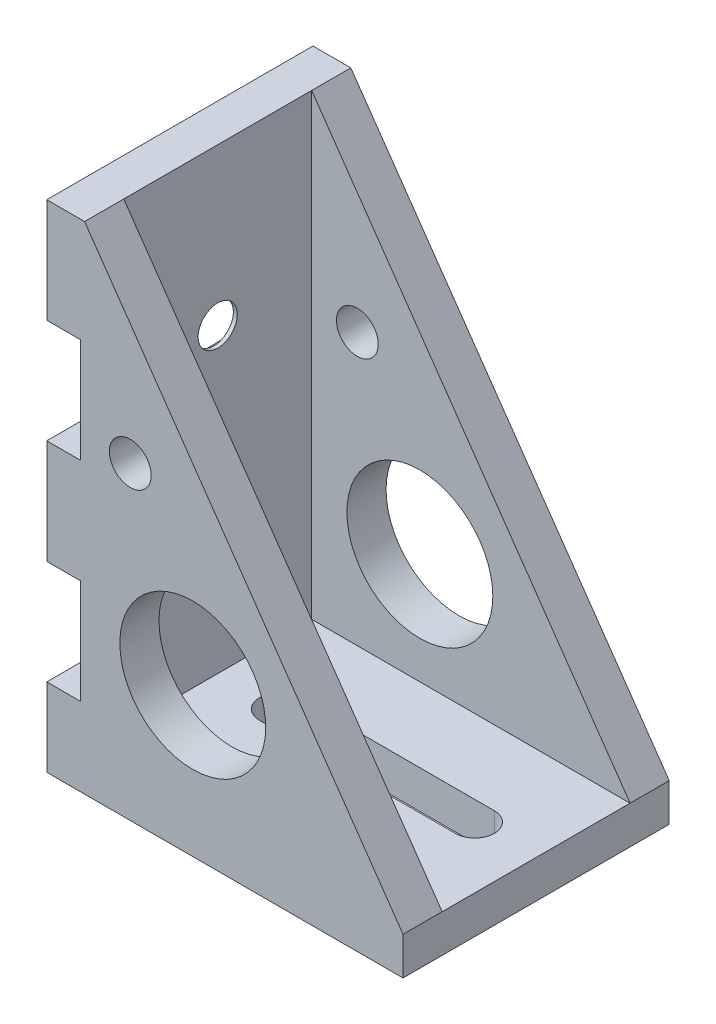
SolidWorks part; units mm, degrees
ref_plane "Alzado" through (0, 0, 0) normal (0, 0, 1) x (1, 0, 0)
ref_plane "Planta" through (0, 0, 0) normal (0, 1, 0) x (1, 0, 0)
ref_plane "Vista lateral" through (0, 0, 0) normal (1, 0, 0) x (0, 0, -1)
sketch "Croquis1" plane through (0, 0, 0) normal (0, 0, 1) x (1, 0, 0)
  line L0 (0, 0) -> (27.3, 0)
  line L1 (27.3, 0) -> (27.3, 2.9)
  line L2 (27.3, 2.9) -> (2.9, 38)
  line L3 (2.9, 38) -> (0, 38)
  line L4 (0, 38) -> (0, 30)
  line L5 (0, 30) -> (2.6, 30)
  line L6 (2.6, 30) -> (2.6, 22)
  line L7 (2.6, 22) -> (0, 22)
  line L8 (0, 22) -> (0, 14)
  line L9 (0, 14) -> (2.6, 14)
  line L10 (2.6, 14) -> (2.6, 6)
  line L11 (2.6, 6) -> (0, 6)
  line L12 (0, 6) -> (0, 0)
  circle A0 centre (11.19, 11.3737) radius 5.59
  circle A1 centre (6.4, 23.7) radius 1.6
  dimension "D7" = 11.18
  dimension "D8" = 3.2
  dimension "D1" = 27.3
  dimension "D2" = 6
  dimension "D3" = 8
  dimension "D4" = 2.6
  dimension "D5" = 2.9
  dimension "D6" = 2.9
  dimension "D9" = 8.59
  dimension "D10" = 11.3737
  dimension "D11" = 3.8
  dimension "D12" = 14.3
extrude "Saliente-Extruir1" add sketch "Croquis1" against normal blind 20.4
sketch "Croquis2" plane through (0, 38, 0) normal (0, 1, 0) x (1, 0, 0)
  line L0 (2.9, 20.4) -> (2.9, 0) construction
  line L1 (2.9, 17.4) -> (27.3, 17.4)
  line L2 (2.9, 17.4) -> (2.9, 3)
  line L3 (2.9, 3) -> (27.3, 3)
  line L4 (27.3, 17.4) -> (27.3, 3)
  line L5 (27.3, 20.4) -> (27.3, 0) construction
  line L6 (27.3, 20.4) -> (2.9, 20.4) construction
  line L7 (27.3, 0) -> (2.9, 0) construction
  dimension "D1" = 3
  dimension "D2" = 3
extrude "Cortar-Extruir1" cut sketch "Croquis2" against normal up to vertex (35.1 mm away)
sketch "Croquis3" plane through (2.6, 0, 0) normal (-1, 0, 0) x (0, 0, 1)
  line L0 (0, 26) -> (-20.4, 26) construction
  line L1 (0, 30) -> (0, 22) construction
  line L2 (-20.4, 30) -> (-20.4, 22) construction
  line L3 (-20.4, 26) -> (-20.4, 10) construction
  line L4 (-20.4, 14) -> (-20.4, 6) construction
  line L5 (-20.4, 10) -> (0, 10) construction
  line L6 (0, 14) -> (0, 6) construction
  circle A0 centre (-10.2, 26) radius 1.5
  circle A1 centre (-10.2, 10) radius 1.5
  dimension "D1" = 3
extrude "Cortar-Extruir2" cut sketch "Croquis3" against normal blind 10
sketch "Croquis4" plane through (0, 2.9, 0) normal (0, 1, 0) x (1, 0, 0)
  line L0 (15.1, 17.4) -> (15.1, 3) construction
  line L1 (27.3, 17.4) -> (2.9, 17.4) construction
  line L2 (2.9, 3) -> (27.3, 3) construction
  line L3 (22.6, 10.2) -> (7.6, 10.2) construction
  line L4 (22.6, 8.7) -> (7.6, 8.7)
  line L5 (22.6, 11.7) -> (7.6, 11.7)
  arc A0 (22.6, 8.7) -> (22.6, 11.7) centre (22.6, 10.2) ccw
  arc A1 (7.6, 11.7) -> (7.6, 8.7) centre (7.6, 10.2) ccw
  point P8 (15.1, 10.2)
  dimension "D2" = 1.5
  dimension "D1" = 15
extrude "Cortar-Extruir3" cut sketch "Croquis4" against normal blind 10
